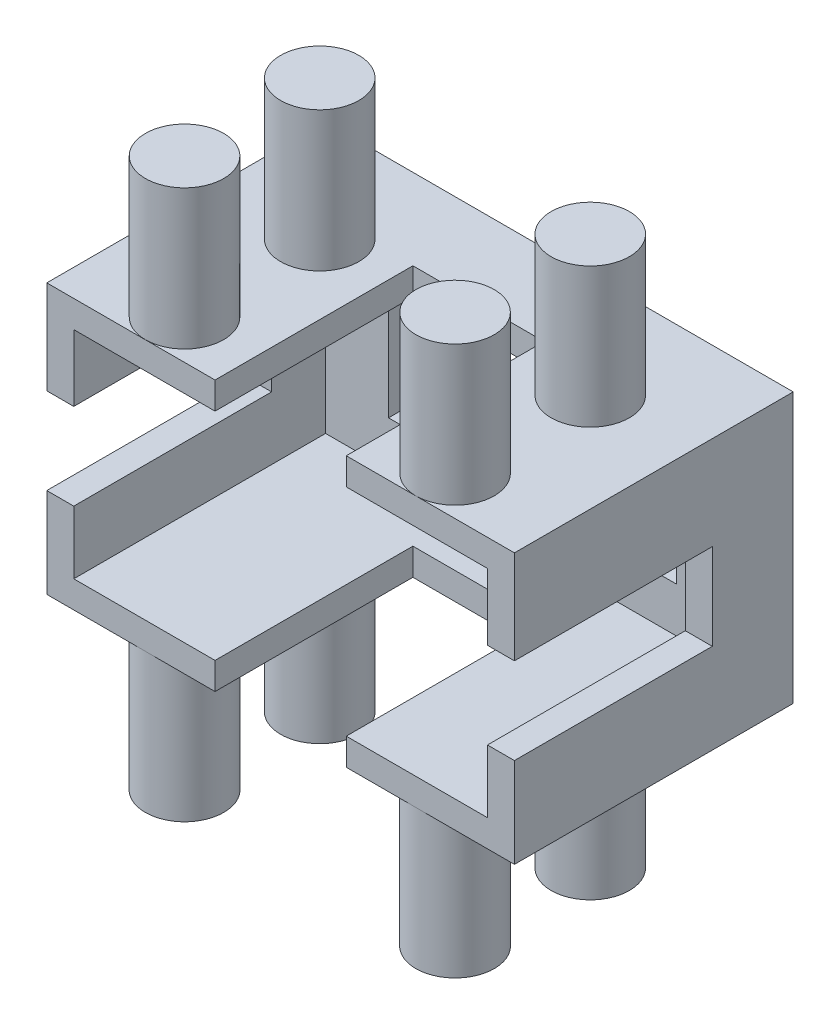
SolidWorks part; units mm, degrees
ref_plane "Front Plane" through (0, 0, 0) normal (0, 0, 1) x (1, 0, 0)
ref_plane "Top Plane" through (0, 0, 0) normal (0, 1, 0) x (1, 0, 0)
ref_plane "Right Plane" through (0, 0, 0) normal (1, 0, 0) x (0, 0, -1)
sketch "Sketch1" plane through (0, 0, 0) normal (0, 0, 1) x (1, 0, 0)
  line L1 (0, 0) -> (26, 0)
  line L2 (0, 0) -> (0, 15)
  line L3 (0, 15) -> (26, 15)
  line L4 (26, 0) -> (26, 15)
  dimension "D1" = 26
  dimension "D2" = 15
extrude "Boss-Extrude1" add sketch "Sketch1" along normal blind 17.4
sketch "Sketch3" plane through (0, 0, 17.4) normal (0, 0, 1) x (1, 0, 0)
  line L0 (0, 0) -> (26, 15) construction
  line L1 (26, 15) -> (26, 0) construction
  line L2 (26, 0) -> (0, 15) construction
  line L4 (1.5, 1.5) -> (24.5, 1.5)
  line L5 (1.5, 1.5) -> (1.5, 13.5)
  line L6 (1.5, 13.5) -> (24.5, 13.5)
  line L7 (24.5, 1.5) -> (24.5, 13.5)
  line L8 (1.5, 1.5) -> (24.5, 13.5) construction
  line L9 (1.5, 13.5) -> (24.5, 1.5) construction
  line L10 (0, 15) -> (0, 0) construction
  line L11 (26, 15) -> (0, 15) construction
  point P4 (13, 7.5)
  dimension "D1" = 1.5
  dimension "D2" = 1.5
extrude "Cut-Extrude1" cut sketch "Sketch3" against normal blind 15.9
sketch "Sketch4" plane through (0, 0, 17.4) normal (0, 0, 1) x (1, 0, 0)
  line L0 (24.5, 1.5) -> (24.5, 0) construction
  line L1 (0, 0) -> (26, 0) construction
  line L2 (24.5, 0) -> (24.5, 15) construction
  line L3 (26, 15) -> (0, 15) construction
  line L4 (24.5, 15) -> (26, 15) construction
  line L5 (26, 15) -> (25.25, 15) construction
  line L6 (25.25, 15) -> (25.25, 0) construction
  line L7 (24.5, 7.5) -> (26, 7.5) construction
  line L8 (26, 0) -> (26, 15) construction
sketch "Sketch5" plane through (0, 0, 0) normal (0, -1, 0) x (1, 0, 0)
  line L0 (0, 8.7) -> (26, 8.7) construction
  line L1 (0, 17.4) -> (0, 0) construction
  line L2 (26, 17.4) -> (26, 0) construction
  line L3 (0, 8.7) -> (1.5, 8.7) construction
  line L4 (13, 17.4) -> (13, 16.8196) construction
  line L5 (0, 17.4) -> (26, 17.4) construction
  line L6 (1.5, 8.7) -> (6.5, 8.7) construction
  line L7 (13, 16.8196) -> (13, 11.8196) construction
  line L8 (13, 0) -> (13, 4.5) construction
  line L9 (0, 0) -> (26, 0) construction
  line L10 (26, 17.4) -> (26, 0) construction
  line L11 (7, 17.4) -> (19, 17.4)
  line L12 (7, 17.4) -> (7, 4.5)
  line L13 (7, 4.5) -> (19, 4.5)
  line L14 (19, 17.4) -> (19, 4.5)
  line L15 (0, 17.4) -> (0, 0) construction
  dimension "D1" = 7
  dimension "D2" = 7
extrude "Cut-Extrude2" cut sketch "Sketch5" against normal blind 15.9
sketch "Sketch6" plane through (0, 0, 0) normal (-1, 0, 0) x (0, 0, 1)
  line L0 (8.7, 15) -> (8.7, 9.8) construction
  line L1 (17.4, 15) -> (0, 15) construction
  line L2 (8.7, 0) -> (8.7, 5) construction
  line L3 (17.4, 0) -> (0, 0) construction
sketch "Sketch8" plane through (0, 0, 0) normal (-1, 0, 0) x (0, 0, 1)
  line L0 (0, 7.5) -> (4.5, 7.5) construction
  line L1 (0, 15) -> (0, 0) construction
  line L2 (8.7, 9.8) -> (17.4, 9.8) construction
  line L3 (17.4, 15) -> (17.4, 0) construction
  line L4 (8.7, 5) -> (17.4, 5) construction
  line L6 (17.4, 9.8) -> (4.5, 9.8)
  line L7 (17.4, 9.8) -> (17.4, 5)
  line L8 (17.4, 5) -> (4.5, 5)
  line L9 (4.5, 9.8) -> (4.5, 5)
extrude "Cut-Extrude4" cut sketch "Sketch8" against normal blind 1000
sketch "Sketch9" plane through (0, 0, 0) normal (0, 0, -1) x (-1, 0, 0)
  line L0 (-26, 7.5) -> (-24.5, 7.5) construction
  line L1 (-24.5, 0) -> (-24.5, 15) construction
  line L2 (-24.5, 7.5) -> (-19.5, 7.5) construction
  line L3 (0, 7.5) -> (-6, 7.5) construction
  line L4 (-13, 15) -> (-13, 10.8) construction
  line L5 (0, 15) -> (0, 0) construction
  line L6 (-26, 15) -> (0, 15) construction
  line L7 (-13, 0) -> (-13, 4) construction
  line L8 (0, 0) -> (-26, 0) construction
  line L9 (-26, 0) -> (-26, 15) construction
  line L10 (-21, 10.8) -> (-5, 10.8)
  line L11 (-21, 10.8) -> (-21, 4)
  line L12 (-21, 4) -> (-5, 4)
  line L13 (-5, 10.8) -> (-5, 4)
  dimension "D1" = 5
  dimension "D2" = 5
extrude "Cut-Extrude5" cut sketch "Sketch9" against normal blind 1000
sketch "Sketch10" plane through (0, 0, 0) normal (-1, 0, 0) x (0, 0, 1)
  line L0 (17.4, 9.8) -> (15.5, 9.8) construction
  line L1 (17.4, 9.8) -> (4.5, 9.8) construction
  line L2 (15.5, 9.8) -> (15.5, 15) construction
  line L3 (17.4, 15) -> (0, 15) construction
  line L5 (15.5, 15) -> (17.4, 15)
  line L6 (15.5, 15) -> (15.5, 0)
  line L7 (15.5, 0) -> (17.4, 0)
  line L8 (17.4, 15) -> (17.4, 0)
extrude "Cut-Extrude6" cut sketch "Sketch10" against normal blind 1000
sketch "Sketch11" plane through (0, 15, 0) normal (0, 1, 0) x (1, 0, 0)
  line L0 (22.5, -15.5) -> (22.5, 0) construction
  line L1 (26, -15.5) -> (19, -15.5) construction
  line L2 (26, 0) -> (0, 0) construction
  line L3 (22.5, -15.5) -> (22.5, -13.325) construction
  line L4 (22.5, -11.15) -> (22.5, -7.98) construction
  line L5 (22.5, -7.98) -> (22.5, -5.805) construction
  line L6 (13, 0) -> (13, -16.4156) construction
  line L7 (20.325, -5.805) -> (18.345, -5.805) construction
  line L8 (20.325, -5.805) -> (20.52, -5.805) construction
  line L9 (20.52, -15.5) -> (20.52, -13.32) construction
  circle A4 centre (20.52, -5.805) radius 2.175
  circle A5 centre (20.52, -13.32) radius 2.175
  circle A6 centre (5.48, -5.805) radius 2.175
  circle A7 centre (5.48, -13.32) radius 2.175
  dimension "D1" = 3.17
extrude "Boss-Extrude2" add sketch "Sketch11" along normal blind 7.76
sketch "Sketch12" plane through (0, 0, 0) normal (0, -1, 0) x (-1, 0, 0)
  line L0 (-3.5, -15.5) -> (-3.5, -13.325) construction
  line L1 (-7, -15.5) -> (0, -15.5) construction
  line L2 (-3.5, -11.15) -> (-3.5, -7.98) construction
  line L3 (-3.5, -7.98) -> (-3.5, -5.805) construction
  line L4 (-13, 0) -> (-13, -16.9452) construction
  line L5 (0, 0) -> (-26, 0) construction
  line L6 (-5.675, -5.805) -> (-7.655, -5.805) construction
  line L7 (-5.675, -5.805) -> (-5.48, -5.805) construction
  line L8 (-5.48, -15.5) -> (-5.48, -13.32) construction
  circle A4 centre (-5.48, -5.805) radius 2.175
  circle A5 centre (-5.48, -13.32) radius 2.18
  circle A6 centre (-20.52, -5.805) radius 2.175
  circle A7 centre (-20.52, -13.32) radius 2.18
  dimension "D1" = 3.17
extrude "Boss-Extrude3" add sketch "Sketch12" along normal blind 7.76
sketch "Sketch13" plane through (0, 15, 0) normal (0, 1, 0) x (1, 0, 0)
  line L1 (19, -4.5) -> (7, -4.5)
  line L2 (19, -4.5) -> (19, -15.5)
  line L3 (19, -15.5) -> (7, -15.5)
  line L4 (7, -4.5) -> (7, -15.5)
extrude "Boss-Extrude5" add sketch "Sketch13" against normal blind 1.5
sketch "Sketch14" plane through (0, 0, 0) normal (0, -1, 0) x (-1, 0, 0)
  line L1 (-19, -4.5) -> (-7, -4.5)
  line L2 (-19, -4.5) -> (-19, -15.5)
  line L3 (-19, -15.5) -> (-7, -15.5)
  line L4 (-7, -4.5) -> (-7, -15.5)
extrude "Boss-Extrude6" add sketch "Sketch14" against normal blind 1.5
sketch "Sketch15" plane through (0, 15, 0) normal (0, 1, 0) x (1, 0, 0)
  line L0 (18.345, -13.32) -> (15.035, -13.32) construction
  circle A0 centre (20.52, -13.32) radius 2.175 construction
sketch "Sketch17" plane through (0, 15, 0) normal (0, 1, 0) x (1, 0, 0)
  line L0 (7.655, -13.32) -> (9.355, -13.32) construction
  line L1 (18.345, -13.32) -> (16.65, -13.32) construction
  line L2 (16.65, 0) -> (16.65, -4.5) construction
  line L3 (26, 0) -> (0, 0) construction
  line L4 (26, -15.5) -> (0, -15.5) construction
  line L5 (16.65, -4.5) -> (9.355, -4.5)
  line L6 (16.65, -4.5) -> (16.65, -15.5)
  line L7 (16.65, -15.5) -> (9.355, -15.5)
  line L8 (9.355, -4.5) -> (9.355, -15.5)
  circle A1 centre (5.48, -13.32) radius 2.175 construction
extrude "Cut-Extrude7" cut sketch "Sketch17" against normal blind 50
